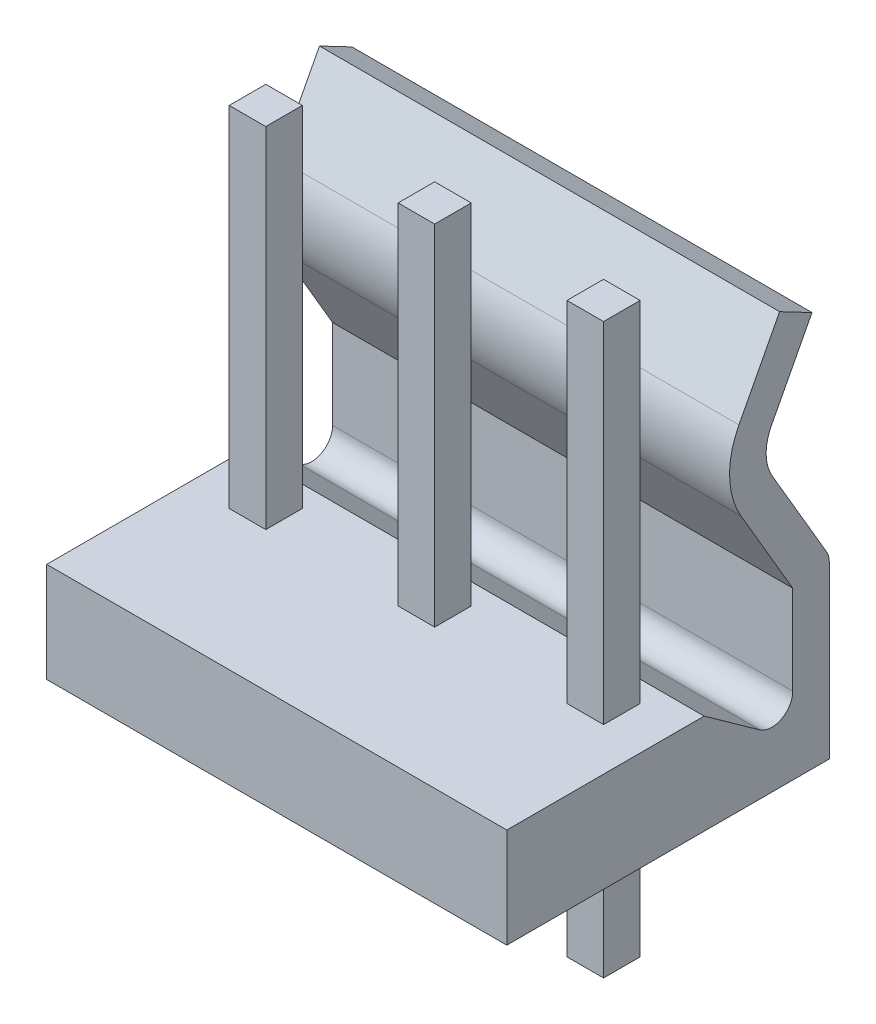
SolidWorks part; units mm, degrees
ref_plane "Alzado" through (0, 0, 0) normal (0, 0, 1) x (1, 0, 0)
ref_plane "Planta" through (0, 0, 0) normal (0, 1, 0) x (1, 0, 0)
ref_plane "Vista lateral" through (0, 0, 0) normal (1, 0, 0) x (0, 0, -1)
sketch "Croquis1" plane through (0, 0, 0) normal (0, 1, 0) x (1, 0, 0)
  line L0 (-1.84, 4.95) -> (12, 4.95)
  line L1 (12, 4.95) -> (12, -4.75)
  line L2 (12, -4.75) -> (-1.84, -4.75)
  line L3 (-1.84, -4.75) -> (-1.84, 4.95)
  line L4 (5.08, -4.75) -> (5.08, 2.1284) construction
  line L5 (-0.55, -0.55) -> (0.55, -0.55)
  line L6 (-0.55, -0.55) -> (-0.55, 0.55)
  line L7 (-0.55, 0.55) -> (0.55, 0.55)
  line L8 (0.55, -0.55) -> (0.55, 0.55)
  line L9 (-0.55, -0.55) -> (0.55, 0.55) construction
  line L10 (-0.55, 0.55) -> (0.55, -0.55) construction
  line L11 (10.71, -0.55) -> (10.71, 0.55)
  line L12 (10.71, -0.55) -> (9.61, -0.55)
  line L13 (9.61, -0.55) -> (9.61, 0.55)
  line L14 (10.71, 0.55) -> (9.61, 0.55)
  line L16 (4.53, -0.55) -> (5.63, -0.55)
  line L17 (4.53, -0.55) -> (4.53, 0.55)
  line L18 (4.53, 0.55) -> (5.63, 0.55)
  line L19 (5.63, -0.55) -> (5.63, 0.55)
  line L20 (4.53, -0.55) -> (5.63, 0.55) construction
  line L21 (4.53, 0.55) -> (5.63, -0.55) construction
  point P5 (0, 0)
  point P16 (0, -0.55)
  point P17 (10.16, -0.55)
  point P18 (5.08, 0)
  dimension "D1" = 13.84
  dimension "D2" = 9.7
  dimension "D3" = 4.75
  dimension "D4" = 10.16
  dimension "D5" = 1.1
  dimension "D6" = 1.1
extrude "Saliente-Extruir1" add sketch "Croquis1" along normal blind 3
sketch "Croquis2" plane through (0, 3, 0) normal (0, 1, 0) x (1, 0, 0)
  line L0 (-1.84, 4.95) -> (-1.84, -4.75) construction
  line L3 (-1.84, 1.95) -> (12, 1.95)
  line L4 (-1.84, 4.95) -> (-1.84, -4.75)
  line L5 (-1.84, -4.75) -> (12, -4.75)
  line L6 (12, -4.75) -> (12, 4.95)
  line L7 (12, 4.95) -> (-1.84, 4.95)
  line L11 (12, 4.95) -> (-1.84, 4.95)
  line L13 (12, -4.75) -> (12, 4.95) construction
  point P2 (2.54, 0.1)
  line M13 (-1.84, 4.95) -> (-1.84, -4.75)
  line M15 (12, -4.75) -> (12, 4.95)
  line M16 (12, 4.95) -> (-1.84, 4.95)
  dimension "D2" = 3
  dimension "D1" = 0
extrude "Saliente-Extruir2" add sketch "Croquis2" along normal blind 9.4 contours L3 M13 M15 M16
sketch "Croquis3" plane through (-1.84, 0, 0) normal (-1, 0, 0) x (0, 0, 1)
  line L1 (-4.95, 5.1309) -> (-4.95, 12.4)
  line L7 (-3.85, 2.32) -> (-3.85, 5)
  line L8 (-3.85, 5) -> (-2.2894, 7.6645)
  line L12 (-4.95, 12.4) -> (-1.95, 12.4) construction
  line L13 (-3.45, 12.4) -> (-1.95, 12.4)
  line L14 (-1.95, 12.4) -> (-1.95, 3)
  line L15 (-1.1844, 3) -> (-2.8543, 1.8075)
  line L16 (-1.95, 3) -> (4.75, 3) construction
  line L17 (-1.95, 3) -> (-1.1844, 3)
  line L18 (-4.95, 12.4) -> (-4.95, 0) construction
  line L19 (-3.4553, 12.4) -> (-2.2323, 10.0635)
  line L20 (-3.4553, 12.4) -> (-4.4299, 11.8899)
  line L21 (-4.4299, 11.8899) -> (-3.2068, 9.5533)
  line L22 (-3.2386, 8.2204) -> (-4.8653, 5.443)
  arc A2 (-3.85, 2.32) -> (-2.8543, 1.8075) centre (-3.2203, 2.32) ccw
  arc A4 (-3.2386, 8.2204) -> (-3.2068, 9.5533) centre (-4.4254, 8.9155) ccw
  arc A5 (-4.8653, 5.443) -> (-4.95, 5.1309) centre (-4.3326, 5.1309) ccw
  arc A6 (-2.2894, 7.6645) -> (-2.2323, 10.0635) centre (-4.4254, 8.9155) ccw
  dimension "D1" = 1.1
  dimension "D2" = 2
  dimension "D3" = 1.1
extrude "Cortar-Extruir1" cut sketch "Croquis3" against normal blind 16.4908
sketch "Croquis5" plane through (0, 0, 0) normal (0, 1, 0) x (1, 0, 0)
  line L0 (10.71, -0.55) -> (10.71, 0.55) construction
  line L1 (9.61, -0.55) -> (10.71, -0.55) construction
  line L2 (9.61, 0.55) -> (9.61, -0.55) construction
  line L3 (10.71, 0.55) -> (9.61, 0.55) construction
  line L4 (0.55, 0.55) -> (-0.55, 0.55) construction
  line L5 (0.55, -0.55) -> (0.55, 0.55) construction
  line L6 (-0.55, -0.55) -> (0.55, -0.55) construction
  line L7 (-0.55, 0.55) -> (-0.55, -0.55) construction
  line L8 (10.71, -0.55) -> (10.71, 0.55)
  line L9 (9.61, -0.55) -> (10.71, -0.55)
  line L10 (9.61, 0.55) -> (9.61, -0.55)
  line L11 (10.71, 0.55) -> (9.61, 0.55)
  line L12 (0.55, 0.55) -> (-0.55, 0.55)
  line L13 (0.55, -0.55) -> (0.55, 0.55)
  line L14 (-0.55, -0.55) -> (0.55, -0.55)
  line L15 (-0.55, 0.55) -> (-0.55, -0.55)
  line L16 (4.53, 0.55) -> (4.53, -0.55) construction
  line L17 (4.53, -0.55) -> (5.63, -0.55) construction
  line L18 (5.63, -0.55) -> (5.63, 0.55) construction
  line L19 (5.63, 0.55) -> (4.53, 0.55) construction
  line L20 (4.53, 0.55) -> (4.53, -0.55)
  line L21 (4.53, -0.55) -> (5.63, -0.55)
  line L22 (5.63, -0.55) -> (5.63, 0.55)
  line L23 (5.63, 0.55) -> (4.53, 0.55)
extrude "Saliente-Extruir3" add sketch "Croquis5" along normal blind 13.5 and the other way blind 3.6
